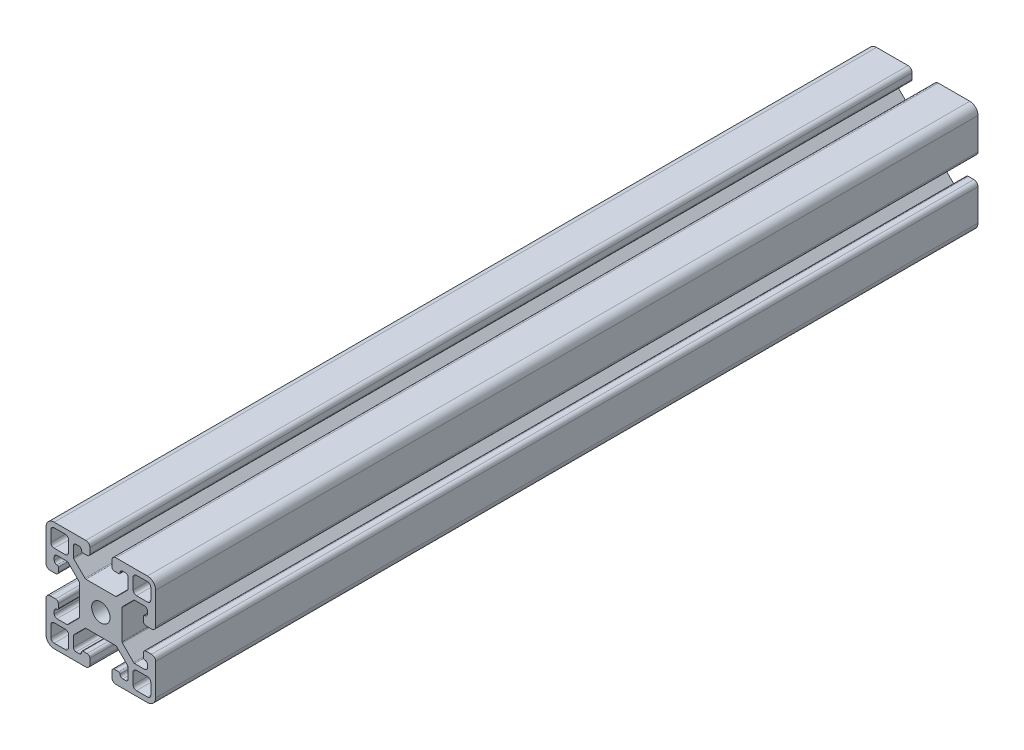
SolidWorks part; units mm, degrees
ref_plane "Front Plane" through (0, 0, 0) normal (0, 0, 1) x (1, 0, 0)
ref_plane "Top Plane" through (0, 0, 0) normal (0, 1, 0) x (1, 0, 0)
ref_plane "Right Plane" through (0, 0, 0) normal (1, 0, 0) x (0, 0, -1)
sketch "Sketch1" plane through (0, 0, 0) normal (0, 0, 1) x (1, 0, 0)
  line B0 (-17, 11.78) -> (-13, 11.78)
  arc B1 (-13, 11.78) -> (-11.78, 13) centre (-13, 13) ccw
  line B2 (-11.78, 13) -> (-11.78, 17)
  arc B3 (-11.78, 17) -> (-13, 18.22) centre (-13, 17) ccw
  line B4 (-13, 18.22) -> (-17, 18.22)
  arc B5 (-17, 18.22) -> (-18.22, 17) centre (-17, 17) ccw
  line B6 (-18.22, 17) -> (-18.22, 13)
  arc B7 (-18.22, 13) -> (-17, 11.78) centre (-17, 13) ccw
  line B8 (-18.22, -13) -> (-18.22, -17)
  arc B9 (-18.22, -17) -> (-17, -18.22) centre (-17, -17) ccw
  line B10 (-17, -18.22) -> (-13, -18.22)
  arc B11 (-13, -18.22) -> (-11.78, -17) centre (-13, -17) ccw
  line B12 (-11.78, -17) -> (-11.78, -13)
  arc B13 (-11.78, -13) -> (-13, -11.78) centre (-13, -13) ccw
  line B14 (-13, -11.78) -> (-17, -11.78)
  arc B15 (-17, -11.78) -> (-18.22, -13) centre (-17, -13) ccw
  line B16 (13, -18.22) -> (17, -18.22)
  arc B17 (17, -18.22) -> (18.22, -17) centre (17, -17) ccw
  line B18 (18.22, -17) -> (18.22, -13)
  arc B19 (18.22, -13) -> (17, -11.78) centre (17, -13) ccw
  line B20 (17, -11.78) -> (13, -11.78)
  arc B21 (13, -11.78) -> (11.78, -13) centre (13, -13) ccw
  line B22 (11.78, -13) -> (11.78, -17)
  arc B23 (11.78, -17) -> (13, -18.22) centre (13, -17) ccw
  line B24 (18.22, 13) -> (18.22, 17)
  arc B25 (18.22, 17) -> (17, 18.22) centre (17, 17) ccw
  line B26 (17, 18.22) -> (13, 18.22)
  arc B27 (13, 18.22) -> (11.78, 17) centre (13, 17) ccw
  line B28 (11.78, 17) -> (11.78, 13)
  arc B29 (11.78, 13) -> (13, 11.78) centre (13, 13) ccw
  line B30 (13, 11.78) -> (17, 11.78)
  arc B31 (17, 11.78) -> (18.22, 13) centre (17, 13) ccw
  line B32 (-9.8536, -11.9786) -> (-5.7714, -7.8964)
  arc B33 (-5.4179, -7.75) -> (-5.7714, -7.8964) centre (-5.4179, -8.25) ccw
  line B34 (-5.4179, -7.75) -> (5.4179, -7.75)
  arc B35 (5.7714, -7.8964) -> (5.4179, -7.75) centre (5.4179, -8.25) ccw
  line B36 (5.7714, -7.8964) -> (9.8536, -11.9786)
  arc B37 (10, -12.3321) -> (9.8536, -11.9786) centre (9.5, -12.3321) ccw
  line B38 (10, -12.3321) -> (10, -16)
  arc B39 (9, -17) -> (10, -16) centre (9, -16) ccw
  line B40 (9, -17) -> (8, -17)
  arc B41 (7, -16) -> (8, -17) centre (8, -16) ccw
  arc B42 (7, -16) -> (6.5, -15.5) centre (6.5, -16) ccw
  line B43 (6.5, -15.5) -> (5, -15.5)
  arc B44 (5, -15.5) -> (4, -16.5) centre (5, -16.5) ccw
  line B45 (4, -16.5) -> (4, -18.5)
  arc B46 (4, -18.5) -> (5.5, -20) centre (5.5, -18.5) ccw
  line B47 (5.5, -20) -> (17, -20)
  arc B48 (17, -20) -> (20, -17) centre (17, -17) ccw
  line B49 (20, -17) -> (20, -5.5)
  arc B50 (20, -5.5) -> (18.5, -4) centre (18.5, -5.5) ccw
  line B51 (18.5, -4) -> (16.5, -4)
  arc B52 (16.5, -4) -> (15.5, -5) centre (16.5, -5) ccw
  line B53 (15.5, -5) -> (15.5, -6.5)
  arc B54 (15.5, -6.5) -> (16, -7) centre (16, -6.5) ccw
  arc B55 (17, -8) -> (16, -7) centre (16, -8) ccw
  line B56 (17, -8) -> (17, -9)
  arc B57 (16, -10) -> (17, -9) centre (16, -9) ccw
  line B58 (16, -10) -> (12.3321, -10)
  arc B59 (11.9786, -9.8536) -> (12.3321, -10) centre (12.3321, -9.5) ccw
  line B60 (11.9786, -9.8536) -> (7.8964, -5.7714)
  arc B61 (7.75, -5.4179) -> (7.8964, -5.7714) centre (8.25, -5.4179) ccw
  line B62 (7.75, -5.4179) -> (7.75, 5.4179)
  arc B63 (7.8964, 5.7714) -> (7.75, 5.4179) centre (8.25, 5.4179) ccw
  line B64 (7.8964, 5.7714) -> (11.9786, 9.8536)
  arc B65 (12.3321, 10) -> (11.9786, 9.8536) centre (12.3321, 9.5) ccw
  line B66 (12.3321, 10) -> (16, 10)
  arc B67 (17, 9) -> (16, 10) centre (16, 9) ccw
  line B68 (17, 9) -> (17, 8)
  arc B69 (16, 7) -> (17, 8) centre (16, 8) ccw
  arc B70 (16, 7) -> (15.5, 6.5) centre (16, 6.5) ccw
  line B71 (15.5, 6.5) -> (15.5, 5)
  arc B72 (15.5, 5) -> (16.5, 4) centre (16.5, 5) ccw
  line B73 (16.5, 4) -> (18.5, 4)
  arc B74 (18.5, 4) -> (20, 5.5) centre (18.5, 5.5) ccw
  line B75 (20, 5.5) -> (20, 17)
  arc B76 (20, 17) -> (17, 20) centre (17, 17) ccw
  line B77 (17, 20) -> (5.5, 20)
  arc B78 (5.5, 20) -> (4, 18.5) centre (5.5, 18.5) ccw
  line B79 (4, 18.5) -> (4, 16.5)
  arc B80 (4, 16.5) -> (5, 15.5) centre (5, 16.5) ccw
  line B81 (5, 15.5) -> (6.5, 15.5)
  arc B82 (6.5, 15.5) -> (7, 16) centre (6.5, 16) ccw
  arc B83 (8, 17) -> (7, 16) centre (8, 16) ccw
  line B84 (8, 17) -> (9, 17)
  arc B85 (10, 16) -> (9, 17) centre (9, 16) ccw
  line B86 (10, 16) -> (10, 12.3321)
  arc B87 (9.8536, 11.9786) -> (10, 12.3321) centre (9.5, 12.3321) ccw
  line B88 (9.8536, 11.9786) -> (5.7714, 7.8964)
  arc B89 (5.4179, 7.75) -> (5.7714, 7.8964) centre (5.4179, 8.25) ccw
  line B90 (5.4179, 7.75) -> (-5.4179, 7.75)
  arc B91 (-5.7714, 7.8964) -> (-5.4179, 7.75) centre (-5.4179, 8.25) ccw
  line B92 (-5.7714, 7.8964) -> (-9.8536, 11.9786)
  arc B93 (-10, 12.3321) -> (-9.8536, 11.9786) centre (-9.5, 12.3321) ccw
  line B94 (-10, 12.3321) -> (-10, 16)
  arc B95 (-9, 17) -> (-10, 16) centre (-9, 16) ccw
  line B96 (-9, 17) -> (-8, 17)
  arc B97 (-7, 16) -> (-8, 17) centre (-8, 16) ccw
  arc B98 (-7, 16) -> (-6.5, 15.5) centre (-6.5, 16) ccw
  line B99 (-6.5, 15.5) -> (-5, 15.5)
  arc B100 (-5, 15.5) -> (-4, 16.5) centre (-5, 16.5) ccw
  line B101 (-4, 16.5) -> (-4, 18.5)
  arc B102 (-4, 18.5) -> (-5.5, 20) centre (-5.5, 18.5) ccw
  line B103 (-5.5, 20) -> (-17, 20)
  arc B104 (-17, 20) -> (-20, 17) centre (-17, 17) ccw
  line B105 (-20, 17) -> (-20, 5.5)
  arc B106 (-20, 5.5) -> (-18.5, 4) centre (-18.5, 5.5) ccw
  line B107 (-18.5, 4) -> (-16.5, 4)
  arc B108 (-16.5, 4) -> (-15.5, 5) centre (-16.5, 5) ccw
  line B109 (-15.5, 5) -> (-15.5, 6.5)
  arc B110 (-15.5, 6.5) -> (-16, 7) centre (-16, 6.5) ccw
  arc B111 (-17, 8) -> (-16, 7) centre (-16, 8) ccw
  line B112 (-17, 8) -> (-17, 9)
  arc B113 (-16, 10) -> (-17, 9) centre (-16, 9) ccw
  line B114 (-16, 10) -> (-12.3321, 10)
  arc B115 (-11.9786, 9.8536) -> (-12.3321, 10) centre (-12.3321, 9.5) ccw
  line B116 (-11.9786, 9.8536) -> (-7.8964, 5.7714)
  arc B117 (-7.75, 5.4179) -> (-7.8964, 5.7714) centre (-8.25, 5.4179) ccw
  line B118 (-7.75, 5.4179) -> (-7.75, -5.4179)
  arc B119 (-7.8964, -5.7714) -> (-7.75, -5.4179) centre (-8.25, -5.4179) ccw
  line B120 (-7.8964, -5.7714) -> (-11.9786, -9.8536)
  arc B121 (-12.3321, -10) -> (-11.9786, -9.8536) centre (-12.3321, -9.5) ccw
  line B122 (-12.3321, -10) -> (-16, -10)
  arc B123 (-17, -9) -> (-16, -10) centre (-16, -9) ccw
  line B124 (-17, -9) -> (-17, -8)
  arc B125 (-16, -7) -> (-17, -8) centre (-16, -8) ccw
  arc B126 (-16, -7) -> (-15.5, -6.5) centre (-16, -6.5) ccw
  line B127 (-15.5, -6.5) -> (-15.5, -5)
  arc B128 (-15.5, -5) -> (-16.5, -4) centre (-16.5, -5) ccw
  line B129 (-16.5, -4) -> (-18.5, -4)
  arc B130 (-18.5, -4) -> (-20, -5.5) centre (-18.5, -5.5) ccw
  line B131 (-20, -5.5) -> (-20, -17)
  arc B132 (-20, -17) -> (-17, -20) centre (-17, -17) ccw
  line B133 (-17, -20) -> (-5.5, -20)
  arc B134 (-5.5, -20) -> (-4, -18.5) centre (-5.5, -18.5) ccw
  line B135 (-4, -18.5) -> (-4, -16.5)
  arc B136 (-4, -16.5) -> (-5, -15.5) centre (-5, -16.5) ccw
  line B137 (-5, -15.5) -> (-6.5, -15.5)
  arc B138 (-6.5, -15.5) -> (-7, -16) centre (-6.5, -16) ccw
  arc B139 (-8, -17) -> (-7, -16) centre (-8, -16) ccw
  line B140 (-8, -17) -> (-9, -17)
  arc B141 (-10, -16) -> (-9, -17) centre (-9, -16) ccw
  line B142 (-10, -16) -> (-10, -12.3321)
  arc B143 (-9.8536, -11.9786) -> (-10, -12.3321) centre (-9.5, -12.3321) ccw
  circle B144 centre (0, 0) radius 3.35
sketch_block_instance "S8-4040 - S-1"
sketch_block "S8-4040 - S"
extrude "Boss-Extrude1" add sketch "Sketch1" along normal blind 300
